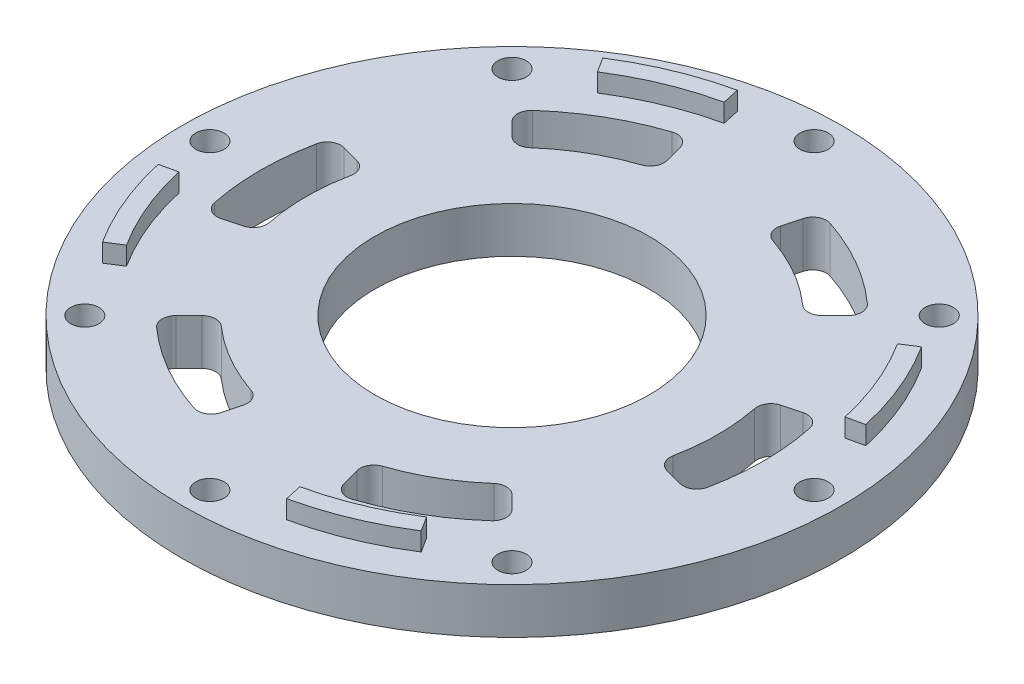
SolidWorks part; units mm, degrees
ref_plane "Front Plane" through (0, 0, 0) normal (0, 0, 1) x (1, 0, 0)
ref_plane "Top Plane" through (0, 0, 0) normal (0, 1, 0) x (1, 0, 0)
ref_plane "Right Plane" through (0, 0, 0) normal (1, 0, 0) x (0, 0, -1)
sketch "Sketch1" plane through (0, 0, 0) normal (0, 1, 0) x (1, 0, 0)
  circle A0 centre (0, 0) radius 36
  dimension "D1" = 72
extrude "Boss-Extrude1" add sketch "Sketch1" along normal blind 5
sketch "Sketch2" plane through (0, 5, 0) normal (0, 1, 0) x (1, 0, 0)
  circle A0 centre (0, 0) radius 15
  dimension "D1" = 30
extrude "Cut-Extrude1" cut sketch "Sketch2" against normal up to surface (5 mm away) up to face at (0, 0, 36)
sketch "Sketch3" plane through (0, 5, 0) normal (0, 1, 0) x (1, 0, 0)
  line L2 (0, 0) -> (0, 10.8819) construction
  line L3 (-15.9099, 15.9099) -> (0, 0) construction
  line L4 (0, 0) -> (-5.8234, 21.7333) construction
  line L5 (-15.9099, 15.9099) -> (-19.4454, 19.4454)
  line L6 (-5.8234, 21.7333) -> (-7.1175, 26.563)
  line L7 (0, 0) -> (-5.3885, 9.3331) construction
  arc A2 (-15.9099, 15.9099) -> (-5.8234, 21.7333) centre (0, 0) ccw construction
  arc A3 (-19.4454, 19.4454) -> (-7.1175, 26.563) centre (0, 0) ccw construction
  arc A4 (-19.4454, 19.4454) -> (-7.1175, 26.563) centre (0, 0) cw
  arc A5 (-15.9099, 15.9099) -> (-5.8234, 21.7333) centre (0, 0) cw
  dimension "D1" = 22.5
  dimension "D2" = 27.5
  dimension "D3" = 30
  dimension "D4" = 15
  dimension "D5" = 15
extrude "Cut-Extrude3" cut sketch "Sketch3" against normal up to surface (5 mm away) up to face at (0, 0, 15)
fillet "Fillet1" radius 1.5 4 edges at (-15.9099, 2.5, -15.9099) (-19.4454, 2.5, -19.4454) (-5.8234, 2.5, -21.7333) (-7.1175, 2.5, -26.563)
pattern_circular "CirPattern1" count 6 over 360 about axis through (0, 0, 0) along (0, 1, 0) of "Cut-Extrude3", "Fillet1"
sketch "Sketch4" plane through (0, 5, 0) normal (0, 1, 0) x (1, 0, 0)
  circle A0 centre (0, 0) radius 33 construction
  circle A1 centre (0, 33) radius 1.55
  dimension "D1" = 66
  dimension "D2" = 3.1
extrude "Cut-Extrude4" cut sketch "Sketch4" against normal up to surface (5 mm away) up to face at (12.2003, 0, -21.1315)
pattern_circular "CirPattern2" count 8 over 360 about axis through (0, 0, 0) along (0, 1, 0) of "Cut-Extrude4"
sketch "Sketch6" plane through (0, 5, 0) normal (0, 1, 0) x (1, 0, 0)
  line L0 (0, 8.8987) -> (0, 0) construction
  line L1 (0, 0) -> (-4.9191, 11.8759) construction
  line L2 (-6.6014, 29.777) -> (0, 0) construction
  line L3 (0, 0) -> (-16.3876, 25.7234) construction
  line L4 (-16.3876, 25.7234) -> (-17.4085, 27.3259)
  line L5 (-6.6014, 29.777) -> (-7.0126, 31.632)
  arc A0 (-7.0126, 31.632) -> (-17.4085, 27.3259) centre (0, 0) ccw
  arc A1 (-6.6014, 29.777) -> (-16.3876, 25.7234) centre (0, 0) ccw
  dimension "D1" = 64.8
  dimension "D3" = 61
  dimension "D2" = 22.5
  dimension "D4" = 10
  dimension "D5" = 10
extrude "Boss-Extrude2" add sketch "Sketch6" along normal blind 2
pattern_circular "CirPattern3" count 4 over 360 about axis through (0, 5, 0) along (0, -1, 0) of "Boss-Extrude2"
